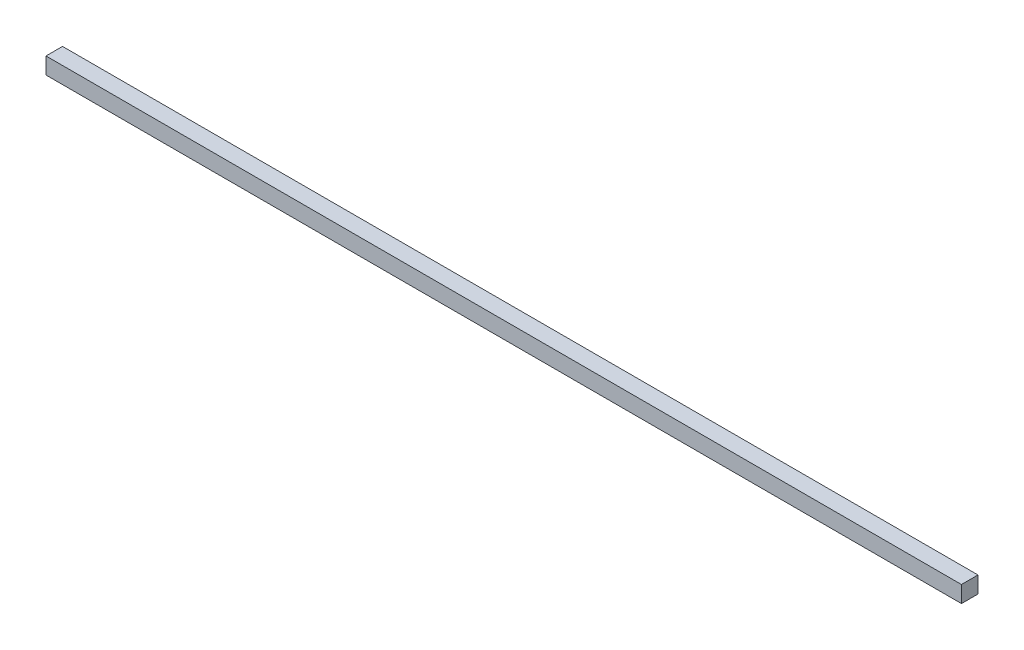
SolidWorks part; units mm, degrees
ref_plane "Front Plane" through (0, 0, 0) normal (0, 0, 1) x (1, 0, 0)
ref_plane "Top Plane" through (0, 0, 0) normal (0, 1, 0) x (1, 0, 0)
ref_plane "Right Plane" through (0, 0, 0) normal (1, 0, 0) x (0, 0, -1)
sketch "Sketch1" plane through (0, 0, 0) normal (1, 0, 0) x (0, 0, -1)
  line L1 (4.6429, -20.8929) -> (24.6429, -20.8929)
  line L2 (4.6429, -20.8929) -> (4.6429, -40.8929)
  line L3 (4.6429, -40.8929) -> (24.6429, -40.8929)
  line L4 (24.6429, -20.8929) -> (24.6429, -40.8929)
  dimension "D1" = 20
  dimension "D2" = 20
extrude "Boss-Extrude1" add sketch "Sketch1" along normal up to surface (1106.8 mm away) from surface
